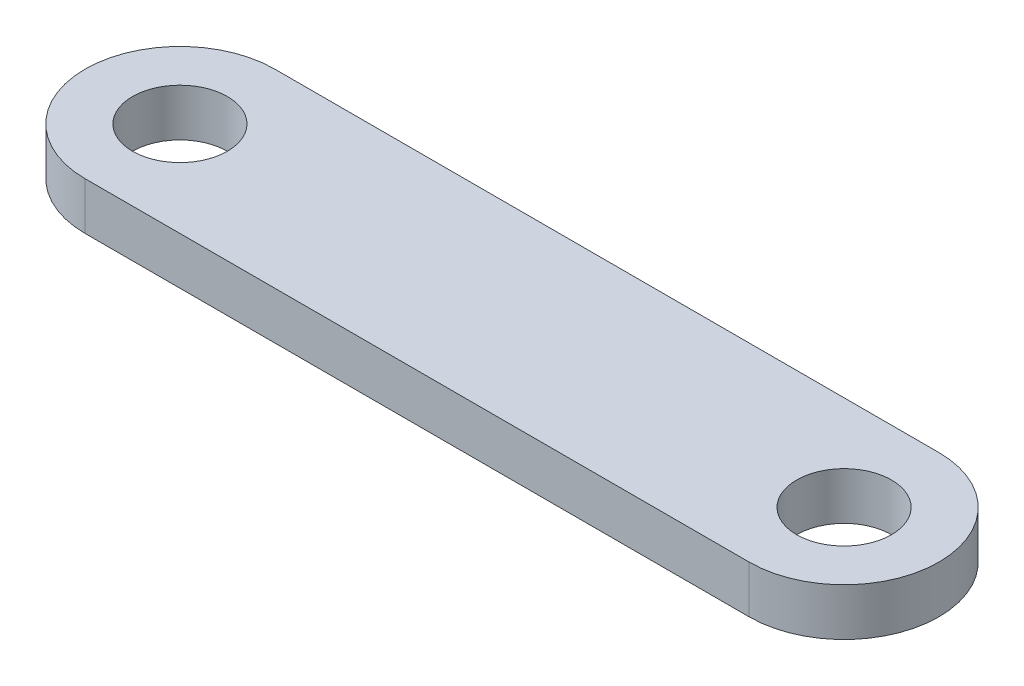
SolidWorks part; units mm, degrees
ref_plane "Ön Düzlem" through (0, 0, 0) normal (0, 0, 1) x (1, 0, 0)
ref_plane "Üst Düzlem" through (0, 0, 0) normal (0, 1, 0) x (1, 0, 0)
ref_plane "Sağ Düzlem" through (0, 0, 0) normal (1, 0, 0) x (0, 0, -1)
sketch "Sketch1" plane through (0, 0, 0) normal (0, 1, 0) x (1, 0, 0)
  line L0 (-35, 0) -> (35, 0) construction
  line L1 (-35, 10) -> (35, 10)
  line L2 (-35, -10) -> (35, -10)
  arc A0 (-35, 10) -> (-35, -10) centre (-35, 0) ccw
  arc A1 (35, -10) -> (35, 10) centre (35, 0) ccw
  circle A2 centre (-35, 0) radius 5
  circle A3 centre (35, 0) radius 5
  point P2 (0, 0)
  dimension "D1" = 10
  dimension "D3" = 10
  dimension "D4" = 10
  dimension "D2" = 70
extrude "Boss-Extrude1" add sketch "Sketch1" along normal blind 5
